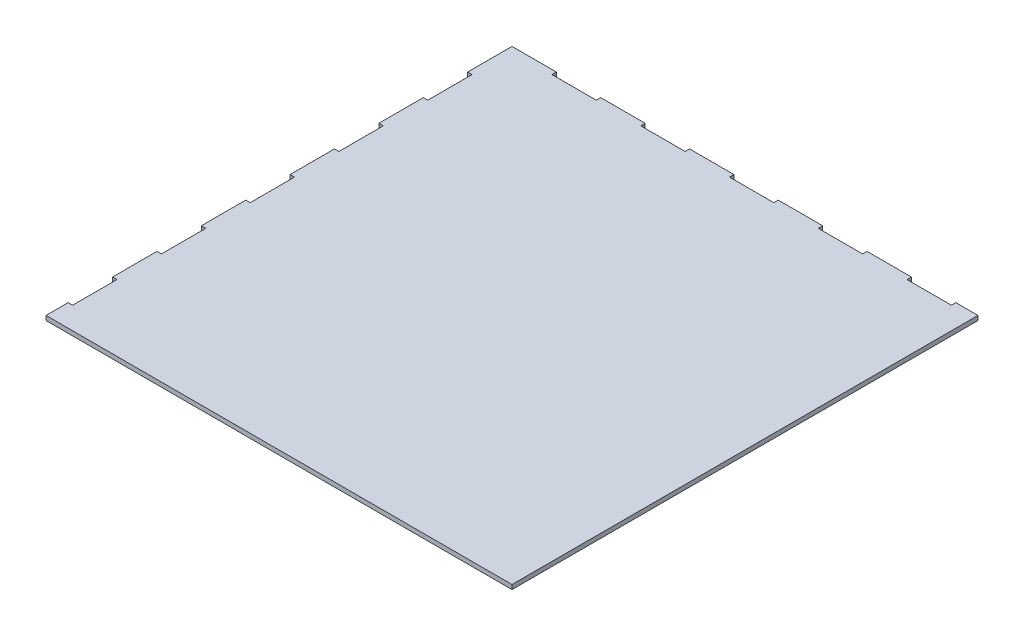
SolidWorks part; units mm, degrees
ref_plane "Front Plane" through (0, 0, 0) normal (0, 0, 1) x (1, 0, 0)
ref_plane "Top Plane" through (0, 0, 0) normal (0, 1, 0) x (1, 0, 0)
ref_plane "Right Plane" through (0, 0, 0) normal (1, 0, 0) x (0, 0, -1)
sketch "Sketch1" plane through (0, 0, 0) normal (0, 1, 0) x (1, 0, 0)
  line L1 (-315, -315) -> (315, -315)
  line L2 (-315, -315) -> (-315, 315)
  line L3 (-315, 315) -> (315, 315)
  line L4 (315, -315) -> (315, 315)
  line L5 (0, 315) -> (0, -315) construction
  line L6 (-315, 0) -> (315, 0) construction
  point P0 (0, 0)
extrude "Boss-Extrude1" add sketch "Sketch1" along normal blind 3
ref_plane "Plane1" through (0, 0, 285) normal (0, 0, 1) x (1, 0, 0)
sketch "Sketch3" plane through (0, 3, 0) normal (0, 1, 0) x (1, 0, 0)
  line L0 (-315, 315) -> (-315, -315) construction
  line L1 (-315, -285.0068) -> (-312, -285.0068)
  line L2 (-315, -285.0068) -> (-315, -255.0068)
  line L3 (-315, -255.0068) -> (-312, -255.0068)
  line L4 (-312, -285.0068) -> (-312, -255.0068)
  dimension "D1" = 30
  dimension "D2" = 3
extrude "Cut-Extrude2" cut sketch "Sketch3" against normal blind 3
pattern_linear "LPattern2" count 10 spacing 60 along (0, 0, -1) of "Cut-Extrude2"
ref_plane "Plane2" through (0, 0, 0) normal (1, 0, 0) x (0, 0, -1)
mirror "Mirror1" about plane through (0, 0, 0) normal (1, 0, 0) of "LPattern2", "Cut-Extrude2"
ref_plane "Plane3" through (-285, 0, 0) normal (-1, 0, 0) x (0, 0, 1)
sketch "Sketch5" plane through (0, 3, 0) normal (0, 1, 0) x (1, 0, 0)
  line L0 (-315, -315) -> (315, -315) construction
  line L1 (-285.0003, -315) -> (-255.0003, -315)
  line L2 (-285.0003, -315) -> (-285.0003, -312)
  line L3 (-285.0003, -312) -> (-255.0003, -312)
  line L4 (-255.0003, -315) -> (-255.0003, -312)
  dimension "D1" = 30
  dimension "D2" = 3
extrude "Cut-Extrude3" cut sketch "Sketch5" against normal blind 3
pattern_linear "LPattern3" count 10 spacing 60 along (1, 0, 0) of "Cut-Extrude3"
ref_plane "Plane4" through (0, 0, 0) normal (0, 0, 1) x (1, 0, 0)
mirror "Mirror2" about plane through (0, 0, 0) normal (0, 0, 1) of "LPattern3", "Cut-Extrude3"
other "SurfaceCut1"
other "SurfaceCut2"
